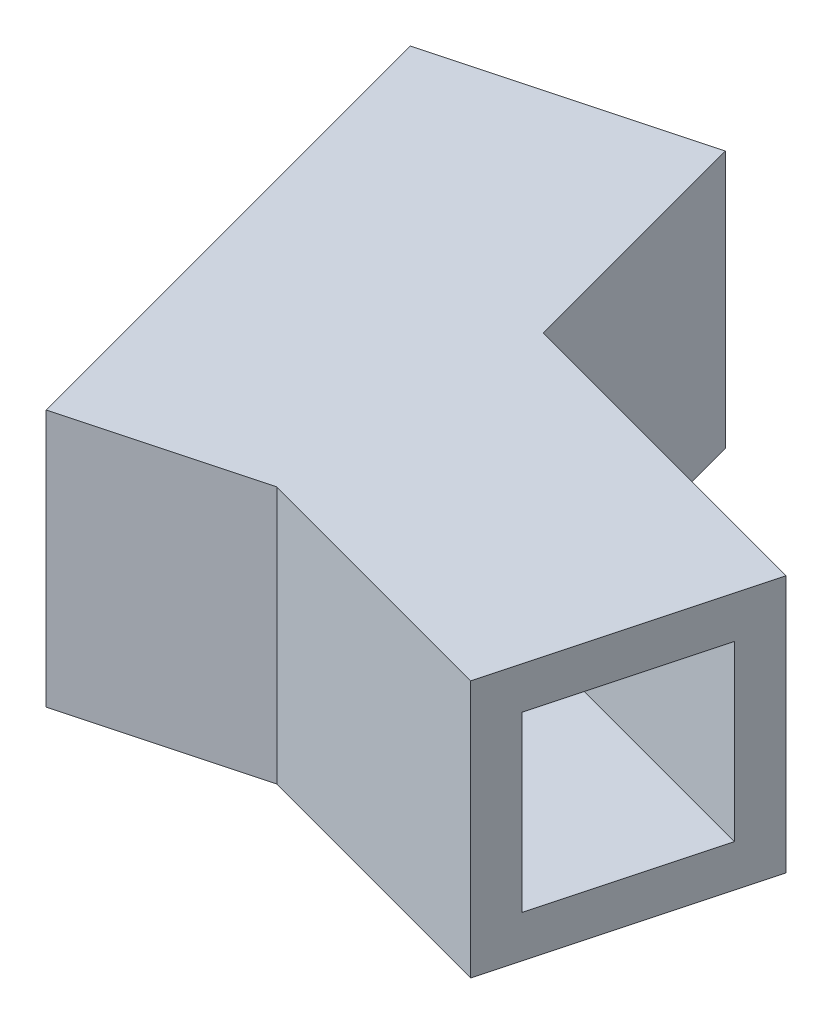
SolidWorks part; units mm, degrees
ref_plane "Спереди" through (0, 0, 0) normal (0, 0, 1) x (1, 0, 0)
ref_plane "Сверху" through (0, 0, 0) normal (0, 1, 0) x (1, 0, 0)
ref_plane "Справа" through (0, 0, 0) normal (1, 0, 0) x (0, 0, -1)
sketch "Sketch1" plane through (0, 0, 0) normal (0, 1, 0) x (1, 0, 0)
  line L0 (-19.3185, 10.3528) -> (-15.4362, -4.1361) construction
  line L1 (0, 0) -> (15.4362, -4.1361)
  line L2 (15.4362, -4.1361) -> (19.3185, 10.3528)
  line L3 (19.3185, 10.3528) -> (0, 15.5291)
  line L4 (0, 15.5291) -> (-19.3185, 10.3528) construction
  line L5 (-15.4362, -4.1361) -> (0, 0) construction
  line L6 (0, 0) -> (0, 15.5291) construction
  line L7 (0, 15.5291) -> (-3.8823, 30.018)
  line L8 (-3.8823, 30.018) -> (-18.3712, 26.1357)
  line L9 (-18.3712, 26.1357) -> (-10.6066, -2.842)
  line L10 (-10.6066, -2.842) -> (0, 0)
  dimension "D1" = 150
  dimension "D2" = 15
  dimension "D3" = 20
  dimension "D4" = 15
  dimension "D5" = 30
extrude "Boss-Extrude1" add sketch "Sketch1" along normal blind 15
sketch "Sketch2" plane through (15.4362, 0, 4.1361) normal (0.9659, 0, 0.2588) x (0.2588, 0, -0.9659)
  line L0 (15, 7.5) -> (0, 7.5) construction
  line L1 (15, 15) -> (15, 0) construction
  line L2 (0, 15) -> (0, 0) construction
  line L4 (2.45, 2.45) -> (12.55, 2.45)
  line L5 (2.45, 2.45) -> (2.45, 12.55)
  line L6 (2.45, 12.55) -> (12.55, 12.55)
  line L7 (12.55, 2.45) -> (12.55, 12.55)
  line L8 (2.45, 2.45) -> (12.55, 12.55) construction
  line L9 (2.45, 12.55) -> (12.55, 2.45) construction
  point P6 (7.5, 7.5)
  dimension "D1" = 10.1
extrude "Cut-Extrude1" cut sketch "Sketch2" against normal blind 18
sketch "Sketch3" plane through (-7.7646, 0, -28.9778) normal (-0.2588, 0, -0.9659) x (-0.9659, 0, 0.2588)
  line L0 (10.9808, 7.5) -> (-4.0192, 7.5) construction
  line L1 (10.9808, 15) -> (10.9808, 0) construction
  line L2 (-4.0192, 15) -> (-4.0192, 0) construction
  line L4 (-1.5692, 12.55) -> (8.5308, 12.55)
  line L5 (-1.5692, 12.55) -> (-1.5692, 2.45)
  line L6 (-1.5692, 2.45) -> (8.5308, 2.45)
  line L7 (8.5308, 12.55) -> (8.5308, 2.45)
  line L8 (-1.5692, 12.55) -> (8.5308, 2.45) construction
  line L9 (-1.5692, 2.45) -> (8.5308, 12.55) construction
  point P6 (3.4808, 7.5)
  dimension "D1" = 10.1
extrude "Cut-Extrude2" cut sketch "Sketch3" against normal blind 17
sketch "Sketch4" plane through (-1.9504, 0, -0.5226) normal (0.9659, 0, 0.2588) x (0.2588, 0, -0.9659)
  line L0 (2.45, 12.55) -> (12.55, 2.45) construction
  line L2 (11.5, 3.5) -> (3.5, 3.5)
  line L3 (11.5, 3.5) -> (11.5, 11.5)
  line L4 (11.5, 11.5) -> (3.5, 11.5)
  line L5 (3.5, 3.5) -> (3.5, 11.5)
  line L6 (11.5, 3.5) -> (3.5, 11.5) construction
  line L7 (11.5, 11.5) -> (3.5, 3.5) construction
  point P4 (7.5, 7.5)
  dimension "D1" = 8
extrude "Cut-Extrude3" cut sketch "Sketch4" against normal up to surface (9.852 mm away)
sketch "Sketch5" plane through (-3.3646, 0, -12.557) normal (-0.2588, 0, -0.9659) x (-0.9659, 0, 0.2588)
  line L0 (8.5308, 2.45) -> (-1.5692, 12.55) construction
  line L2 (-0.5192, 3.5) -> (7.4808, 3.5)
  line L3 (-0.5192, 3.5) -> (-0.5192, 11.5)
  line L4 (-0.5192, 11.5) -> (7.4808, 11.5)
  line L5 (7.4808, 3.5) -> (7.4808, 11.5)
  line L6 (-0.5192, 3.5) -> (7.4808, 11.5) construction
  line L7 (-0.5192, 11.5) -> (7.4808, 3.5) construction
  point P4 (3.4808, 7.5)
  point P9 (0, 0)
  dimension "D1" = 8
extrude "Cut-Extrude4" cut sketch "Sketch5" against normal up to surface (9.2583 mm away)
fillet "Fillet1" radius 6 1 edges at (-10.5608, 7.5, -6.4532)
fillet "Fillet2" radius 3 8 edges at (-11.5311, 11.5, -10.0742) (-11.5311, 3.5, -10.0742) (-9.9045, 3.5, -7.1096) (-4.1297, 11.5, -4.73) (-9.9045, 11.5, -7.1096) (-0.9159, 11.5, -12.1511) (-0.9159, 3.5, -12.1511) (-4.1297, 3.5, -4.73)
